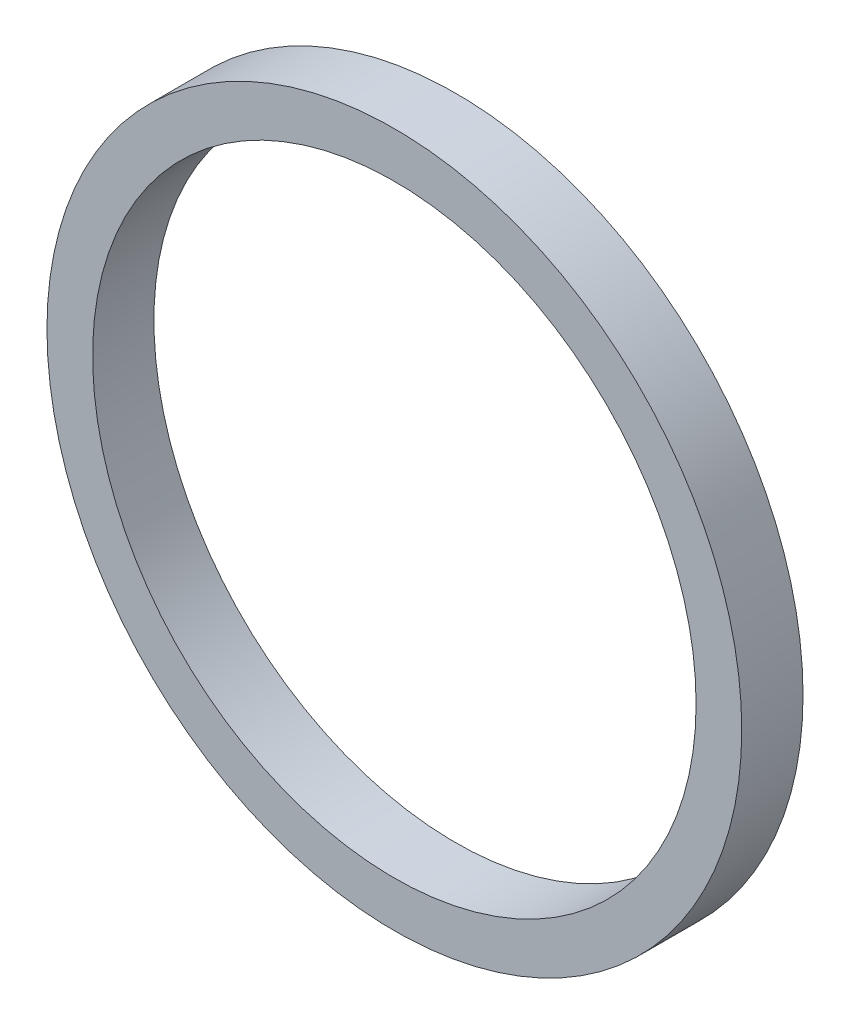
SolidWorks part; units mm, degrees
ref_plane "Front Plane" through (0, 0, 0) normal (0, 0, 1) x (1, 0, 0)
ref_plane "Top Plane" through (0, 0, 0) normal (0, 1, 0) x (1, 0, 0)
ref_plane "Right Plane" through (0, 0, 0) normal (1, 0, 0) x (0, 0, -1)
sketch "Sketch1" plane through (0, 0, 0) normal (0, 1, 0) x (1, 0, 0)
  line L0 (4.2479, -1.5081) -> (4.2479, -0.7588)
  line L1 (4.2479, -0.7588) -> (3.6896, -0.7588)
  line L2 (3.6896, -0.7588) -> (3.6896, -1.5081)
  line L3 (3.6896, -1.5081) -> (4.2479, -1.5081)
  line L4 (0, -0.7588) -> (0, -1.5081) construction
revolve "Revolve1" add sketch "Sketch1" angle 360 about L4
